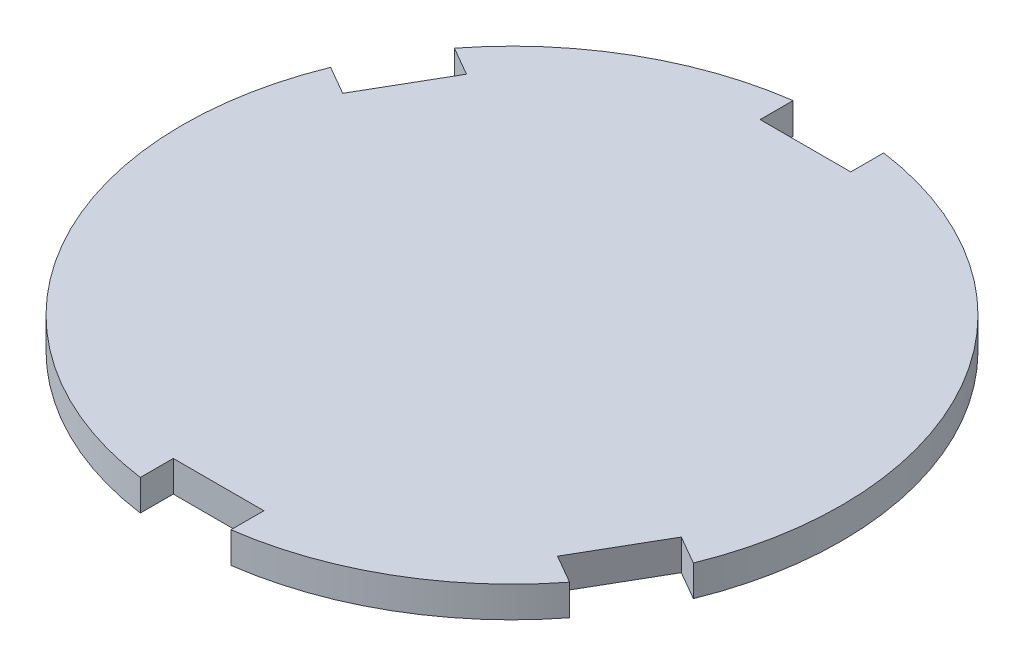
SolidWorks part; units mm, degrees
material "6061-T6 (SS)"
ref_plane "Front Plane" through (0, 0, 0) normal (0, 0, 1) x (1, 0, 0)
ref_plane "Top Plane" through (0, 0, 0) normal (0, 1, 0) x (1, 0, 0)
ref_plane "Right Plane" through (0, 0, 0) normal (1, 0, 0) x (0, 0, -1)
sketch "Sketch1" plane through (0, 0, 0) normal (0, 1, 0) x (1, 0, 0)
  circle A0 centre (0, 0) radius 50.8
  dimension "D1" = 101.6
extrude "Boss-Extrude1" add sketch "Sketch1" along normal blind 4.7625
sketch "Sketch2" plane through (0, 4.7625, 0) normal (0, 1, 0) x (1, 0, 0)
  line L0 (0, 0) -> (0, -55.8813) construction
  line L1 (0, 0) -> (59.2491, 0) construction
  line L2 (-6.985, -45.2375) -> (6.985, -45.2375)
  line L3 (6.985, -45.2375) -> (6.985, -50.3175)
  line L4 (-6.985, -45.2375) -> (-6.985, -50.3175)
  line L5 (-6.985, 45.2375) -> (-6.985, 50.3175)
  line L6 (-6.985, 45.2375) -> (6.985, 45.2375)
  line L7 (6.985, 45.2375) -> (6.985, 50.3175)
  circle A0 centre (0, 0) radius 50.8 construction
  arc A1 (-6.985, -50.3175) -> (6.985, -50.3175) centre (0, 0) ccw
  arc A2 (-6.985, 50.3175) -> (6.985, 50.3175) centre (0, 0) cw
  point P7 (0, -45.2375)
  dimension "D1" = 13.97
  dimension "D2" = 5.08
extrude "Cut-Extrude1" cut sketch "Sketch2" against normal up to next
sketch "Sketch3" plane through (0, 4.7625, 0) normal (0, 1, 0) x (1, 0, 0)
  line L0 (0, 0) -> (49.3026, -28.4649) construction
  line L1 (0, 0) -> (26.5906, 46.0563) construction
  line L2 (0, -55) -> (0, 55) construction
  line L3 (35.6843, -28.6679) -> (42.6693, -16.5696)
  line L4 (35.6843, -28.6679) -> (40.0837, -31.2079)
  line L5 (42.6693, -16.5696) -> (47.0687, -19.1096)
  line L6 (-35.6843, 28.6679) -> (-40.0837, 31.2079)
  line L7 (-42.6693, 16.5696) -> (-35.6843, 28.6679)
  line L8 (-42.6693, 16.5696) -> (-47.0687, 19.1096)
  arc A0 (6.985, -50.3175) -> (6.985, 50.3175) centre (0, 0) ccw construction
  arc A1 (47.0687, -19.1096) -> (40.0837, -31.2079) centre (0, 0) cw
  arc A2 (-40.0837, 31.2079) -> (-47.0687, 19.1096) centre (0, 0) ccw
  point P7 (39.1768, -22.6187)
  dimension "D1" = 60
  dimension "D2" = 13.97
  dimension "D3" = 5.08
extrude "Cut-Extrude2" cut sketch "Sketch3" against normal up to next
equation "\"bulkhead\"=4"
equation "\"D1@Sketch1\"=\"bulkhead\""
